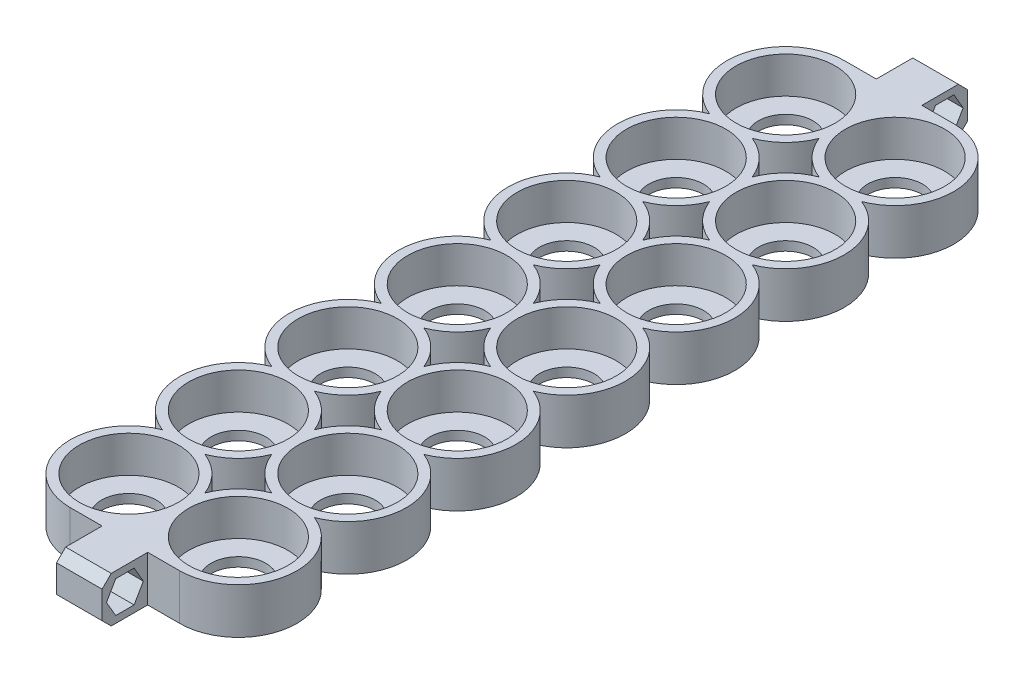
SolidWorks part; units mm, degrees
ref_plane "Front Plane" through (0, 0, 0) normal (0, 0, 1) x (1, 0, 0)
ref_plane "Top Plane" through (0, 0, 0) normal (0, 1, 0) x (1, 0, 0)
ref_plane "Right Plane" through (0, 0, 0) normal (1, 0, 0) x (0, 0, -1)
sketch "Sketch1" plane through (0, 0, 0) normal (1, 0, 0) x (0, 0, -1)
  line L0 (0, 27.0772) -> (0, -22.0037) construction
  line L1 (-12.875, 5) -> (-12.875, -5)
  line L2 (-12.875, -5) -> (-6, -5)
  line L3 (-6, -5) -> (-6, -3)
  line L4 (-6, -3) -> (-10.875, -3)
  line L5 (-10.875, -3) -> (-10.875, 5)
  line L6 (-10.875, 5) -> (-12.875, 5)
  point P5 (-12.875, 0)
  dimension "D1" = 10
  dimension "D2" = 2
  dimension "D3" = 21.75
  dimension "D4" = 12
  dimension "D5" = 2
revolve "Revolve1" add sketch "Sketch1" angle 360 about L0
sketch "Sketch2" plane through (0, -5, 0) normal (0, -1, 0) x (1, 0, 0)
  line L0 (0, 12.1827) -> (0, -11.4982) construction
pattern_linear "LPattern1" count 7 spacing 24 along (0, 0, -1) of "Revolve1"
sketch "Sketch3" plane through (0, -5, 0) normal (0, -1, 0) x (1, 0, 0)
  line L0 (-17.2986, 0) -> (17.8169, 0) construction
pattern_linear "LPattern2" count 2 spacing 24 along (1, 0, 0) of "Revolve1", "LPattern1"
ref_plane "Plane1" through (0, 0, 12.875) normal (0, 0, 1) x (1, 0, 0)
sketch "Sketch4" plane through (0, 0, 12.875) normal (0, 0, 1) x (1, 0, 0)
  line L0 (12, 5) -> (12, -5) construction
  line L1 (12, 5) -> (-12.875, 5) construction
  line L2 (24, -5) -> (0, -5)
  line L3 (24, -5) -> (24, 5)
  line L4 (24, 5) -> (0, 5)
  line L5 (0, -5) -> (0, 5)
  line L6 (24, -5) -> (0, 5) construction
  line L7 (24, 5) -> (0, -5) construction
  point P4 (12, 0)
  dimension "D1" = 24
extrude "Boss-Extrude1" add sketch "Sketch4" against normal up to next
sketch "Sketch5" plane through (0, 0, 12.875) normal (0, 0, 1) x (1, 0, 0)
  line L0 (12, 5) -> (12, -5) construction
  line L1 (24, 5) -> (0, 5) construction
  line L2 (0, -5) -> (24, -5) construction
  line L8 (17, -5) -> (7, -5)
  line L9 (17, -5) -> (17, 5)
  line L10 (17, 5) -> (7, 5)
  line L11 (7, -5) -> (7, 5)
  line L12 (17, -5) -> (7, 5) construction
  line L13 (17, 5) -> (7, -5) construction
  point P6 (12, 0)
  point P7 (12, 0)
  dimension "D1" = 10
  dimension "D2" = 10
extrude "Boss-Extrude2" add sketch "Sketch5" along normal blind 10
sketch "Sketch8" plane through (7, 0, 0) normal (-1, 0, 0) x (0, 0, 1)
  line L0 (12.875, 0) -> (22.875, 0) construction
  line L1 (12.875, -3.3) -> (12.875, 3.3) construction
  line L2 (22.875, 5) -> (22.875, -5) construction
  line L3 (17.875, 5) -> (17.875, -5) construction
  line L4 (22.875, 5) -> (12.875, 5) construction
  line L5 (22.875, -5) -> (12.875, -5) construction
  line L7 (19.8957, -3.5) -> (21.9165, 0)
  line L8 (21.9165, 0) -> (19.8957, 3.5)
  line L9 (19.8957, 3.5) -> (15.8543, 3.5)
  line L10 (15.8543, 3.5) -> (13.8335, 0)
  line L11 (13.8335, 0) -> (15.8543, -3.5)
  line L12 (15.8543, -3.5) -> (19.8957, -3.5)
  circle A0 centre (17.875, 0) radius 3.5 construction
  point P13 (0, 0)
  dimension "D1" = 7
extrude "Cut-Extrude1" cut sketch "Sketch8" against normal up to surface (10 mm away) up to face at (17, 0, 17.875)
chamfer "Chamfer3" distance 2 angle 45 2 edges at (12, -5, 22.875) (12, 5, 22.875)
ref_plane "Plane2" through (12.875, 0, 0) normal (1, 0, 0) x (0, 0, -1)
ref_plane "Plane3" through (0, 0, -66) normal (0, 0, -1) x (-1, 0, 0)
ref_plane "Plane4" through (0, 0, -78) normal (0, 0, 1) x (1, 0, 0)
ref_plane "Plane5" through (0, 0, -72) normal (0, 0, 1) x (1, 0, 0)
mirror "Mirror2" about plane through (0, 0, -72) normal (0, 0, 1) of "Boss-Extrude1", "Chamfer3", "Cut-Extrude1", "Boss-Extrude2"
